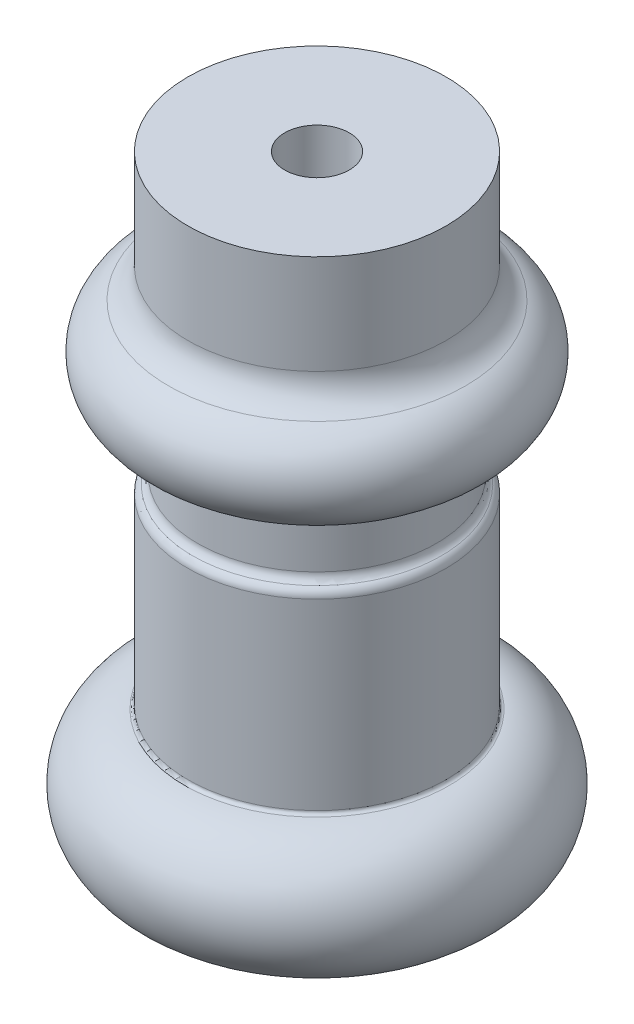
SolidWorks part; units mm, degrees
ref_plane "Front Plane" through (0, 0, 0) normal (0, 0, 1) x (1, 0, 0)
ref_plane "Top Plane" through (0, 0, 0) normal (0, 1, 0) x (1, 0, 0)
ref_plane "Right Plane" through (0, 0, 0) normal (1, 0, 0) x (0, 0, -1)
sketch "Sketch1" plane through (0, 0, 0) normal (0, 0, 1) x (1, 0, 0)
  line L0 (-12.0473, 34.344) -> (-12.0473, -90.656)
  line L1 (-9.9251, -90.656) -> (49990.0749, -90.656) construction
  line L2 (-12.0473, -59.0452) -> (-12.0473, -50059.0452) construction
  line L3 (-12.0473, 34.344) -> (-2.0473, 34.344)
  line L4 (-2.0473, 34.344) -> (-2.0473, 97.2115)
  line L5 (-2.0473, 97.2115) -> (27.9527, 97.2115)
  line L6 (27.9527, 97.2115) -> (27.9527, 66.4662)
  line L7 (24.9527, 25.5534) -> (24.9527, 10.5534)
  line L8 (27.9527, 5.3572) -> (27.9527, -51.3373)
  line L9 (-12.0473, -90.656) -> (35.1404, -90.656)
  arc A0 (33.9527, 57.3011) -> (27.9527, 28.5534) centre (27.9527, 43.5534) cw
  arc A1 (27.9527, 28.5534) -> (24.9527, 25.5534) centre (27.9527, 25.5534) ccw
  arc A2 (24.9527, 10.5534) -> (26.4527, 7.9553) centre (27.9527, 10.5534) ccw
  arc A3 (26.4527, 7.9553) -> (27.9527, 5.3572) centre (24.9527, 5.3572) cw
  arc A4 (27.9527, -51.3373) -> (28.9292, -52.4054) centre (29.025, -51.3373) ccw
  arc A5 (28.9292, -52.4054) -> (35.1404, -90.656) centre (27.1413, -72.3253) cw
  arc A6 (27.9527, 66.4662) -> (33.9527, 57.3011) centre (37.9527, 66.4662) ccw
  point P26 (25.8314, 27.6747)
  dimension "D1" = 10
  dimension "D2" = 15
  dimension "D6" = 20
  dimension "D7" = 10
  dimension "D3" = 100
  dimension "D4" = 30
  dimension "D5" = 62.8675
  dimension "D8" = 125
revolve "Revolve2" add sketch "Sketch1" angle 360 about L2
